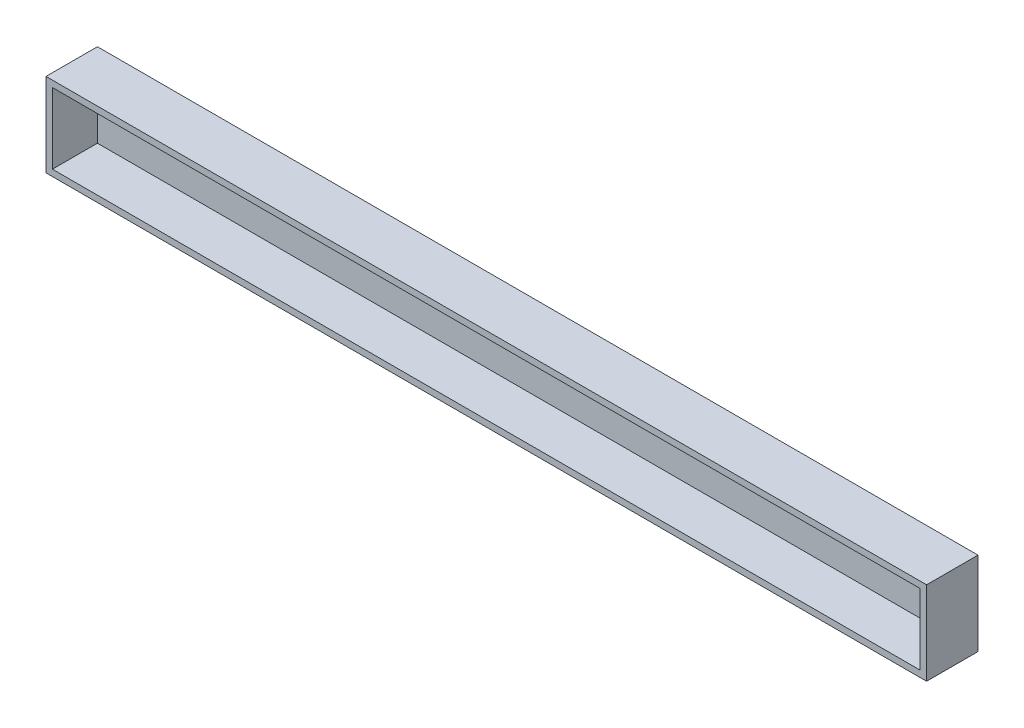
SolidWorks part; units mm, degrees
ref_plane "Front Plane" through (0, 0, 0) normal (0, 0, 1) x (1, 0, 0)
ref_plane "Top Plane" through (0, 0, 0) normal (0, 1, 0) x (1, 0, 0)
ref_plane "Right Plane" through (0, 0, 0) normal (1, 0, 0) x (0, 0, -1)
sketch "Sketch1" plane through (0, 0, 0) normal (0, 0, 1) x (1, 0, 0)
  line L1 (0, 0) -> (137, 0)
  line L2 (0, 0) -> (0, 13)
  line L3 (0, 13) -> (137, 13)
  line L4 (137, 0) -> (137, 13)
  line L6 (1, 1) -> (136, 1)
  line L7 (1, 1) -> (1, 12)
  line L8 (1, 12) -> (136, 12)
  line L9 (136, 1) -> (136, 12)
  dimension "D1" = 1
  dimension "D2" = 136
  dimension "D3" = 137
  dimension "D4" = 1
  dimension "D5" = 12
  dimension "D6" = 13
extrude "Profile" add sketch "Sketch1" along normal blind 8
sketch "Sketch2" plane through (0, 0, 0) normal (0, 0, 1) x (1, 0, 0)
  line L1 (1, 1) -> (136, 1)
  line L2 (1, 1) -> (1, 12)
  line L3 (1, 12) -> (136, 12)
  line L4 (136, 1) -> (136, 12)
  dimension "D1" = 135
  dimension "D2" = 11
extrude "Back" add sketch "Sketch2" along normal blind 1
equation "\"Profile_Depth\"= 8mm"
equation "\"D1@Profile\" = \"Profile_Depth\""
equation "\"Profile_Sketch_1\"= 1mm"
equation "\"D1@Sketch1\" = \"Profile_Sketch_1\""
equation "\"Profile_Sketch_2\"= 136mm"
equation "\"D2@Sketch1\" = \"Profile_Sketch_2\""
equation "\"Profile_Sketch_3\"= 137mm"
equation "\"D3@Sketch1\" = \"Profile_Sketch_3\""
equation "\"Profile_Sketch_4\"= 1mm"
equation "\"D4@Sketch1\" = \"Profile_Sketch_4\""
equation "\"Profile_Sketch_5\"= 12mm"
equation "\"D5@Sketch1\" = \"Profile_Sketch_5\""
equation "\"Profile_Sketch_6\"= 13mm"
equation "\"D6@Sketch1\" = \"Profile_Sketch_6\""
equation "\"Back_Depth\"= 1mm"
equation "\"D1@Back\" = \"Back_Depth\""
equation "\"Back_Sketch_1\"= 135mm"
equation "\"D1@Sketch2\" = \"Back_Sketch_1\""
equation "\"Back_Sketch_2\"= 11mm"
equation "\"D2@Sketch2\" = \"Back_Sketch_2\""
equation "\"EnvelopeWidth\"= 137mm"
equation "\"EnvelopeHeight\"= 13mm"
